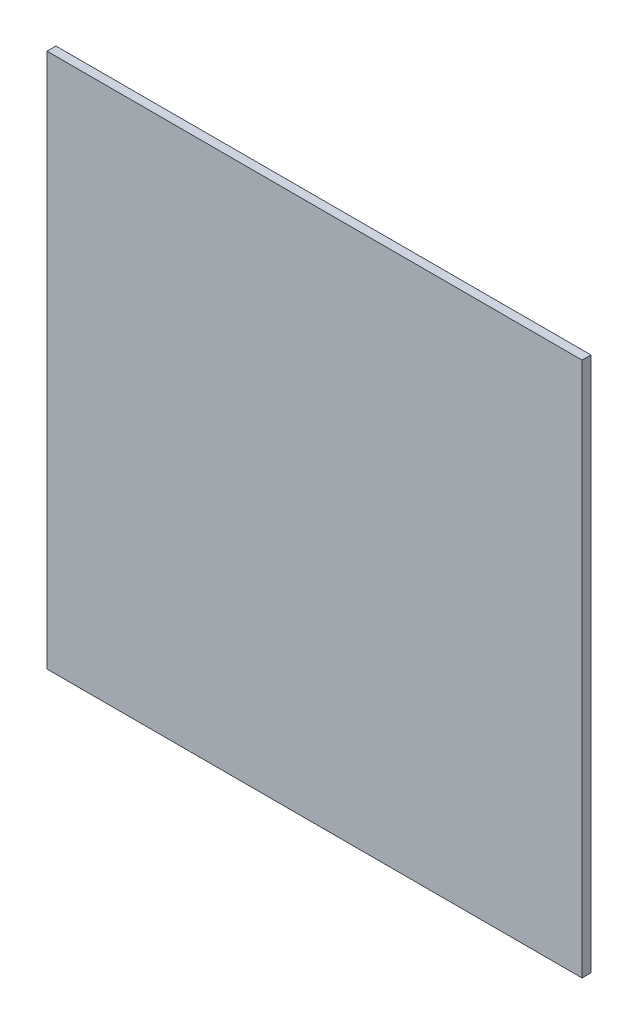
SolidWorks part; units mm, degrees
other "Marcação1"
sketch "Esboço1" plane through (0, 0, 0) normal (0, 0, 1) x (1, 0, 0)
ref_plane "Plano frontal" through (0, 0, 0) normal (0, 0, 1) x (1, 0, 0)
ref_plane "Plano superior" through (0, 0, 0) normal (0, 1, 0) x (1, 0, 0)
ref_plane "Plano direito" through (0, 0, 0) normal (1, 0, 0) x (0, 0, -1)
sketch "Esboço2" plane through (0, 0, 0) normal (0, 0, 1) x (1, 0, 0)
  line L1 (90, -90) -> (-90, -90)
  line L2 (90, -90) -> (90, 90)
  line L3 (90, 90) -> (-90, 90)
  line L4 (-90, -90) -> (-90, 90)
  line L5 (90, -90) -> (-90, 90) construction
  line L6 (90, 90) -> (-90, -90) construction
  point P0 (0, 0)
  dimension "D1" = 180
  dimension "D2" = 180
extrude "Ressalto-extrusão1" add sketch "Esboço2" along normal blind 3
